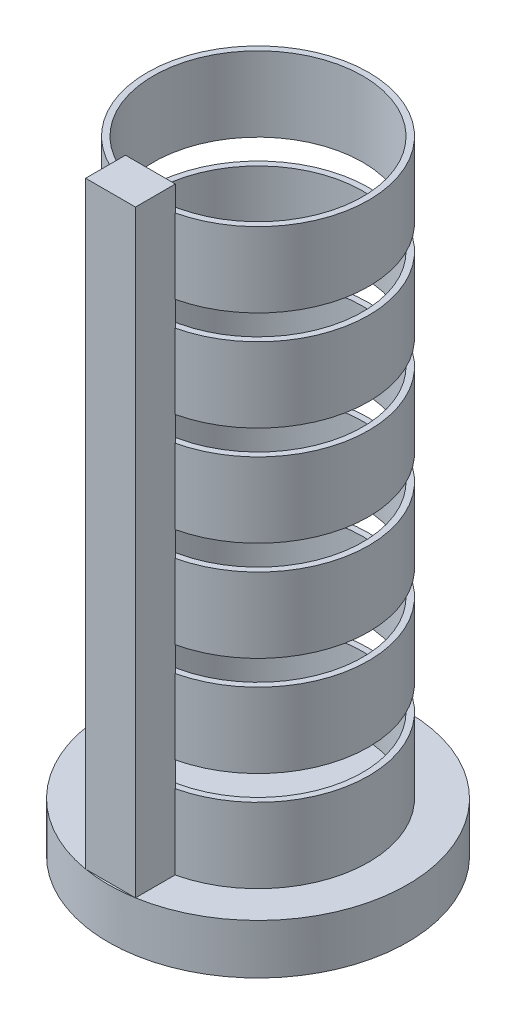
SolidWorks part; units mm, degrees
ref_plane "Front Plane" through (0, 0, 0) normal (0, 0, 1) x (1, 0, 0)
ref_plane "Top Plane" through (0, 0, 0) normal (0, 1, 0) x (1, 0, 0)
ref_plane "Right Plane" through (0, 0, 0) normal (1, 0, 0) x (0, 0, -1)
sketch "Sketch2" plane through (0, 0, 0) normal (0, 1, 0) x (1, 0, 0)
  circle A0 centre (0, 0) radius 38.1
  dimension "D1" = 38.1
extrude "Boss-Extrude1" add sketch "Sketch2" along normal blind 12.7
sketch "Sketch3" plane through (0, 12.7, 0) normal (0, 1, 0) x (1, 0, 0)
  line L0 (0, -27.4071) -> (0, -37.5671) construction
  line L1 (-6.35, -27.4071) -> (6.35, -27.4071)
  line L2 (-6.35, -27.4071) -> (-6.35, -37.5671)
  line L3 (-6.35, -37.5671) -> (6.35, -37.5671)
  line L4 (6.35, -27.4071) -> (6.35, -37.5671)
  line L5 (-6.35, -32.4871) -> (6.1043, -32.4871) construction
  circle A0 centre (0, 0) radius 38.1 construction
  point P10 (0, 0)
  dimension "D1" = 12.7
  dimension "D2" = 10.16
extrude "Boss-Extrude2" add sketch "Sketch3" along normal blind 152.4
sketch "Sketch4" plane through (0, 12.7, 0) normal (0, 1, 0) x (1, 0, 0)
  circle A0 centre (0, 0) radius 26.67
  point P3 (0, 0)
  dimension "D1" = 53.34
sketch "Sketch5" plane through (0, 0, 0) normal (0, 0, 1) x (1, 0, 0)
  line L0 (0, 12.7) -> (0, 31.75)
  dimension "D1" = 19.05
sweep "Sweep-Thin1" add profiles "Sketch4" path "Sketch5" parameters "D1"=1.524
pattern_linear "LPattern1" count 6 spacing 25.4 along (0, 1, 0) of "Sweep-Thin1"
